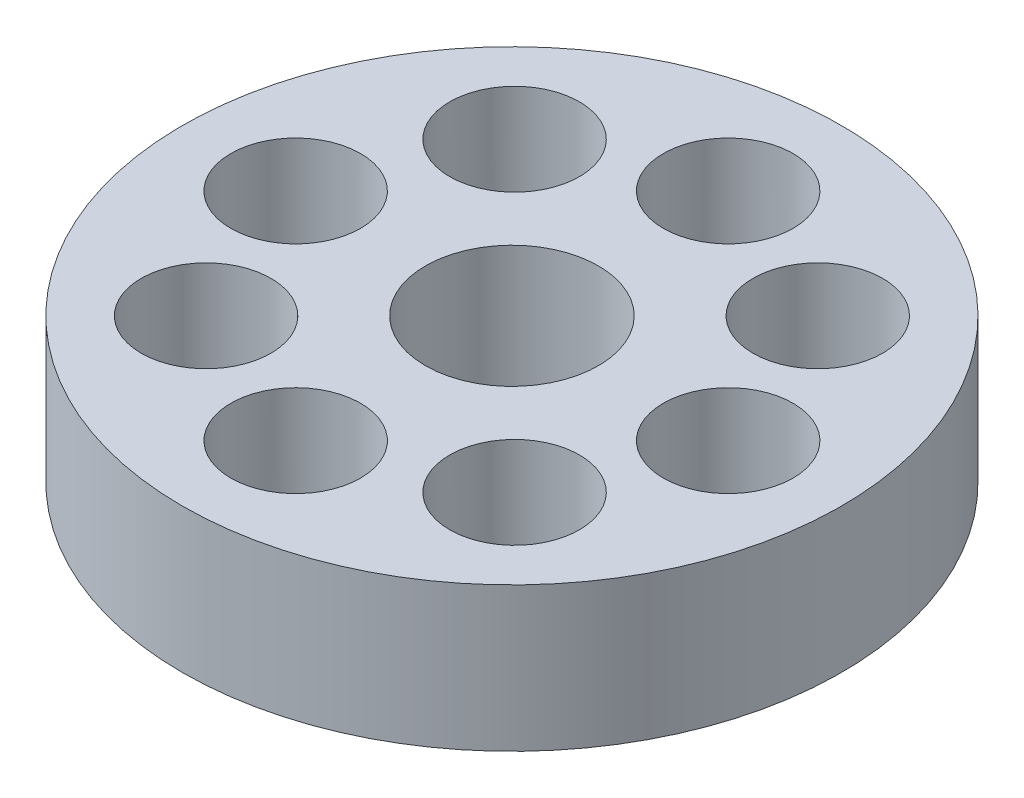
SolidWorks part; units mm, degrees
ref_plane "Front Plane" through (0, 0, 0) normal (0, 0, 1) x (1, 0, 0)
ref_plane "Top Plane" through (0, 0, 0) normal (0, 1, 0) x (1, 0, 0)
ref_plane "Right Plane" through (0, 0, 0) normal (1, 0, 0) x (0, 0, -1)
sketch "Sketch1" plane through (0, 0, 0) normal (0, 1, 0) x (1, 0, 0)
  line L0 (0, -164.5173) -> (0, 163.7587) construction
  line L1 (-114.3, 0) -> (190.5902, 0) construction
  line L2 (-147.7915, -147.7875) -> (81.9046, 81.9086) construction
  line L3 (101.4928, -100.577) -> (-132.9305, 133.8463) construction
  circle A0 centre (0, 0) radius 114.3
  circle A1 centre (75, 0) radius 22.5
  circle A3 centre (53.031, 53.035) radius 22.5
  circle A4 centre (0, 75) radius 22.5
  circle A5 centre (-52.5731, 53.4889) radius 22.5
  circle A6 centre (-75, 0) radius 22.5
  circle A7 centre (-53.035, -53.031) radius 22.5
  circle A8 centre (0, -75) radius 22.5
  circle A10 centre (53.4889, -52.5731) radius 22.5
  circle A11 centre (0, 0) radius 30
  dimension "D1" = 228.6
  dimension "D4" = 45
  dimension "D5" = 75
  dimension "D7" = 75
  dimension "D8" = 75
  dimension "D9" = 75
  dimension "D10" = 75
  dimension "D11" = 75
  dimension "D12" = 75
  dimension "D14" = 60
  dimension "D2" = 45
  dimension "D3" = 45
  dimension "D6" = 75
  dimension "D13" = 75
extrude "Boss-Extrude1" add sketch "Sketch1" along normal blind 50
sketch "Sketch2" plane through (0, 50, 0) normal (0, 1, 0) x (1, 0, 0)
  circle A0 centre (0, 0) radius 60
  circle A1 centre (0, 0) radius 90
  dimension "D1" = 120
  dimension "D2" = 180
extrude "Cut-Extrude1" cut sketch "Sketch2" against normal blind 20 from offset 35 offset against normal yes
